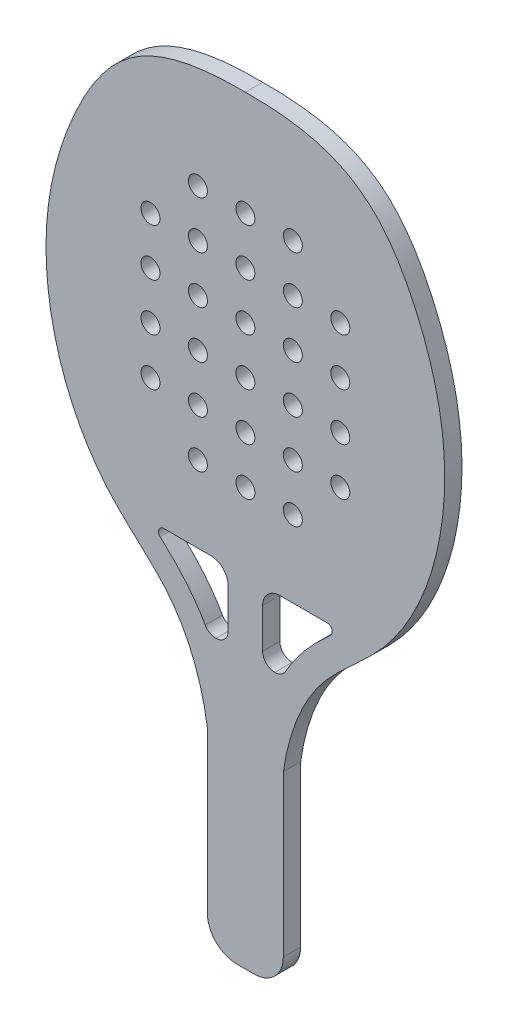
SolidWorks part; units mm, degrees
ref_plane "Piano frontale" through (0, 0, 0) normal (0, 0, 1) x (1, 0, 0)
ref_plane "Piano superiore" through (0, 0, 0) normal (0, 1, 0) x (1, 0, 0)
ref_plane "Piano destro" through (0, 0, 0) normal (1, 0, 0) x (0, 0, -1)
sketch "Schizzo4" plane through (0, 0, 0) normal (0, 0, 1) x (1, 0, 0)
  line L12 (-279.8508, -255.338) -> (-301.8508, -255.338)
  line L15 (-279.8508, -365.338) -> (-301.8508, -365.338)
  line L16 (-301.8508, -255.338) -> (-301.8508, -365.338)
  line L17 (-334.851, -167.9164) -> (-299.8512, -167.9164)
  line L18 (-257.8508, -255.338) -> (-257.8508, -365.338)
  line L19 (-279.8508, -365.338) -> (-257.8508, -365.338)
  line L22 (-279.8508, 71.662) -> (-279.8508, -365.338) construction
  line L24 (-289.8512, -177.9164) -> (-289.8512, -207.9165)
  line L25 (-289.8512, -207.9165) -> (-301.1902, -207.9165)
  line L26 (-269.8504, -207.9165) -> (-258.5114, -207.9165)
  line L27 (-269.8504, -177.9164) -> (-269.8504, -207.9165)
  line L28 (-224.8506, -167.9164) -> (-259.8504, -167.9164)
  circle A30 centre (-224.8508, -41.1306) radius 5.5
  circle A31 centre (-279.8508, -123.6306) radius 5.5
  circle A32 centre (-334.8508, -96.1306) radius 5.5
  circle A33 centre (-279.8508, -13.6306) radius 5.5
  circle A34 centre (-334.8508, -13.6306) radius 5.5
  circle A36 centre (-252.3508, 13.8694) radius 5.5
  circle A37 centre (-224.8508, -68.6306) radius 5.5
  circle A38 centre (-252.3508, -41.1306) radius 5.5
  circle A39 centre (-334.8508, -41.1306) radius 5.5
  circle A40 centre (-279.8508, -68.6306) radius 5.5
  circle A42 centre (-224.8508, -13.6306) radius 5.5
  circle A43 centre (-252.3508, -96.1306) radius 5.5
  circle A44 centre (-307.3508, -41.1306) radius 5.5
  circle A46 centre (-307.3508, -123.6306) radius 5.5
  circle A47 centre (-252.3508, -13.6306) radius 5.5
  circle A48 centre (-252.3508, -68.6306) radius 5.5
  circle A49 centre (-307.3508, -68.6306) radius 5.5
  circle A50 centre (-279.8508, -96.1306) radius 5.5
  circle A51 centre (-307.3508, 13.8694) radius 5.5
  circle A52 centre (-252.3508, -123.6306) radius 5.5
  circle A53 centre (-307.3508, -96.1306) radius 5.5
  circle A54 centre (-307.3508, -13.6306) radius 5.5
  circle A56 centre (-279.8508, -41.1306) radius 5.5
  circle A57 centre (-334.8508, -68.6306) radius 5.5
  circle A58 centre (-279.8508, 13.8694) radius 5.5
  circle A59 centre (-224.8508, -96.1306) radius 5.5
  arc A60 (-299.8512, -167.9164) -> (-289.8512, -177.9164) centre (-299.8512, -177.9164) cw
  arc A61 (-259.8504, -167.9164) -> (-269.8504, -177.9164) centre (-259.8504, -177.9164) ccw
  spline S2 degree 3 poles (-279.8508, 74.662) (-315.2385, 74.9846) (-351.6886, 64.5005) (-386.7804, 3.1266) (-403.9074, -72.627) (-376.8108, -156.4491) (-317.1845, -200.1024) (-304.6889, -235.5968) (-301.8508, -255.338) knots 0 0 0 0 0.150071 0.226929 0.372737 0.578941 0.665353 0.775035 0.775035 0.775035 0.775035
  spline S3 degree 3 poles (-279.8508, 74.662) (-244.4631, 74.9846) (-208.013, 64.5005) (-172.9212, 3.1266) (-155.7943, -72.627) (-182.8908, -156.4491) (-242.5171, -200.1024) (-255.0127, -235.5968) (-257.8508, -255.338) knots 0 0 0 0 0.150071 0.226929 0.372737 0.578941 0.665353 0.775035 0.775035 0.775035 0.775035
  spline S4 degree 1 poles (-279.9875, 59.6626) (-287.0035, -253.2034) knots 0 0 1 1 construction
  spline S5 degree 3 poles (-279.9875, 59.6626) (-280.6553, 59.6687) (-281.9986, 59.6755) (-284.6228, 59.6663) (-287.8296, 59.6125) (-291.5476, 59.4795) (-296.3374, 59.2101) (-302.0111, 58.7002) (-308.3296, 57.8106) (-314.1728, 56.6457) (-321.3596, 54.7293) (-329.2792, 51.6638) (-337.4282, 46.8786) (-343.4488, 41.8003) (-347.9729, 36.8874) (-352.4067, 31.2893) (-357.6573, 23.2096) (-362.3928, 14.1388) (-365.8467, 6.5608) (-369.0321, -1.0625) (-372.4929, -10.6621) (-376.9036, -26.1767) (-380.2673, -45.8462) (-380.7139, -70.0136) (-377.412, -94.5904) (-371.5571, -114.3255) (-365.0607, -129.1191) (-359.3005, -139.5849) (-353.7855, -147.6705) (-348.9386, -153.7209) (-345.1295, -157.9881) (-340.9569, -162.1975) (-334.9272, -167.8955) (-326.7382, -175.2928) (-319.1067, -182.7984) (-314.2009, -188.4104) (-310.989, -192.3522) (-305.7639, -199.5797) (-299.5064, -210.5451) (-293.7241, -224.4365) (-290.2259, -236.3598) (-288.1518, -245.9888) (-287.3506, -250.7887) (-287.0035, -253.2034) knots 0 0 0 0 0.003027 0.006055 0.01211 0.018165 0.02422 0.03633 0.04844 0.06055 0.07266 0.096879 0.121099 0.145319 0.157429 0.169539 0.193759 0.217979 0.230088 0.242198 0.266418 0.290638 0.339078 0.387517 0.435957 0.484397 0.508617 0.532836 0.557056 0.569166 0.581276 0.593386 0.605496 0.629716 0.653936 0.659991 0.666045 0.678155 0.702375 0.726595 0.750815 0.762925 0.775035 0.775035 0.775035 0.775035 only from (-334.851, -167.9164) to (-301.1902, -207.9165)
  spline S6 degree 3 poles (-224.8506, -167.9164) (-227.4885, -170.3513) (-233.5197, -175.8403) (-240.5948, -182.7986) (-245.5006, -188.4105) (-248.7125, -192.3523) (-253.3269, -198.735) (-256.6547, -204.3718) (-258.5116, -207.9165) knots 0.60947 0.60947 0.60947 0.60947 0.629716 0.653936 0.659991 0.666045 0.678155 0.697421 0.697421 0.697421 0.697421
  dimension "D20" = 110
  dimension "D21" = 10
extrude "Estrusione-Estrusione3" add sketch "Schizzo4" along normal blind 10 separate body
fillet "Raccordo3" radius 17 2 edges at (-257.8508, -365.338, 5) (-301.8508, -365.338, 5)
fillet "Raccordo4" radius 3 2 edges at (-334.851, -167.9164, 5) (-224.8506, -167.9164, 5)
fillet "Raccordo5" radius 7 4 edges at (-289.8512, -207.9165, 5) (-301.1902, -207.9165, 5) (-258.5116, -207.9165, 5) (-269.8504, -207.9165, 5)
